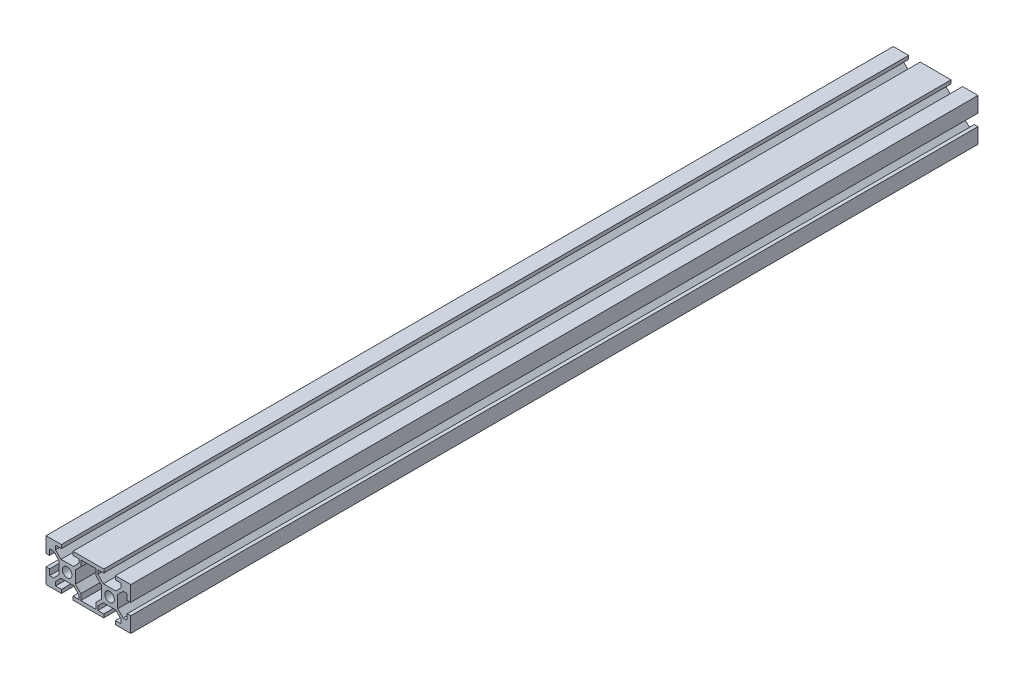
SolidWorks part; units mm, degrees
ref_plane "前视基准面" through (0, 0, 0) normal (0, 0, 1) x (1, 0, 0)
ref_plane "上视基准面" through (0, 0, 0) normal (0, 1, 0) x (1, 0, 0)
ref_plane "右视基准面" through (0, 0, 0) normal (1, 0, 0) x (0, 0, -1)
sketch "草图1" plane through (0, 0, 0) normal (0, 0, 1) x (1, 0, 0)
  line L0 (-4.1, 15) -> (-4.1, 12.5)
  line L1 (-4.3858, -5.8) -> (4.3858, -5.8)
  line L2 (-5.8, -4.3858) -> (-5.8, 4.3858)
  line L3 (-4.3858, 5.8) -> (4.3858, 5.8)
  line L4 (5.8, -4.3858) -> (5.8, 4.3858)
  line L5 (-9.6642, 8.25) -> (-12.5, 8.25)
  line L6 (-8.25, -12.5) -> (-4.1, -12.5)
  line L7 (-15, -15) -> (-4.1, -15)
  line L8 (-15, -15) -> (-15, -4.1)
  line L9 (-8.25, 15) -> (-4.1, 15)
  line L10 (9.6642, -8.25) -> (9.6642, -12.5)
  line L11 (-8.25, 9.6642) -> (-8.25, 12.5)
  line L12 (-8.25, 15) -> (-15, 15)
  line L13 (9.6642, -12.5) -> (20.3358, -12.5)
  line L14 (8.25, 9.6642) -> (8.25, 12.5)
  line L15 (8.25, 15) -> (15, 15)
  line L16 (20.3358, -12.5) -> (20.3358, -8.25)
  line L17 (9.6642, 8.25) -> (9.6642, 12.5)
  line L18 (8.25, -9.6642) -> (8.25, -12.5)
  line L19 (8.25, -15) -> (15, -15)
  line L20 (9.6642, 12.5) -> (20.3358, 12.5)
  line L21 (-15, 8.25) -> (-15, 15)
  line L22 (-9.6642, -8.25) -> (-12.5, -8.25)
  line L23 (-8.25, -9.6642) -> (-8.25, -12.5)
  line L24 (-8.25, -15) -> (-15, -15)
  line L25 (-15, -8.25) -> (-15, -15)
  line L26 (-12.5, -8.25) -> (-12.5, -4.1)
  line L27 (-8.25, 12.5) -> (-4.1, 12.5)
  line L28 (20.3358, 12.5) -> (20.3358, 8.25)
  line L29 (-8.25, 9.6642) -> (-4.3858, 5.8)
  line L30 (-9.6642, 8.25) -> (-5.8, 4.3858)
  line L31 (8.25, 9.6642) -> (4.3858, 5.8)
  line L32 (9.6642, 8.25) -> (5.8, 4.3858)
  line L33 (4.3858, -5.8) -> (8.25, -9.6642)
  line L34 (-5.8, -4.3858) -> (-9.6642, -8.25)
  line L35 (4.1, 15) -> (4.1, 12.5)
  line L36 (5.8, -4.3858) -> (9.6642, -8.25)
  line L37 (-4.3858, -5.8) -> (-8.25, -9.6642)
  line L38 (4.1, 15) -> (15, 15)
  line L39 (4.1, 12.5) -> (8.25, 12.5)
  line L40 (-4.1, -12.5) -> (-4.1, -15)
  line L41 (4.1, -15) -> (15, -15)
  line L42 (4.1, -12.5) -> (8.25, -12.5)
  line L43 (4.1, -12.5) -> (4.1, -15)
  line L44 (-15, 4.1) -> (-12.5, 4.1)
  line L45 (-15, -4.1) -> (-12.5, -4.1)
  line L46 (-15, 4.1) -> (-15, 15)
  line L47 (-12.5, 4.1) -> (-12.5, 8.25)
  line L48 (-15, -15) -> (0, 0) construction
  line L52 (-15, 8.25) -> (-15, 4.1)
  line L54 (8.25, -15) -> (4.1, -15)
  line L55 (8.25, 15) -> (4.1, 15)
  line L56 (38.25, 9.6642) -> (38.25, 12.5)
  line L57 (21.75, 9.6642) -> (25.6142, 5.8)
  line L58 (38.25, -15) -> (34.1, -15)
  line L59 (25.6142, 5.8) -> (34.3858, 5.8)
  line L61 (34.1, 15) -> (34.1, 12.5)
  line L62 (21.75, 15) -> (15, 15)
  line L63 (39.6642, 8.25) -> (35.8, 4.3858)
  line L64 (45, 4.1) -> (45, 15)
  line L65 (38.25, 15) -> (45, 15)
  line L66 (39.6642, -8.25) -> (42.5, -8.25)
  line L68 (45, -15) -> (45, -4.1)
  line L69 (38.25, -9.6642) -> (38.25, -12.5)
  line L70 (35.8, -4.3858) -> (39.6642, -8.25)
  line L71 (42.5, -4.1) -> (45, -4.1)
  line L72 (45, 8.25) -> (45, 15)
  line L73 (42.5, -8.25) -> (42.5, -4.1)
  line L74 (38.25, 15) -> (34.1, 15)
  line L77 (34.1, 12.5) -> (38.25, 12.5)
  line L79 (38.25, 9.6642) -> (34.3858, 5.8)
  line L80 (34.1, -12.5) -> (38.25, -12.5)
  line L82 (35.8, -4.3858) -> (35.8, 4.3858)
  line L83 (21.75, -15) -> (15, -15)
  line L84 (34.1, -15) -> (45, -15)
  line L85 (21.75, -12.5) -> (25.9, -12.5)
  line L86 (39.6642, 8.25) -> (42.5, 8.25)
  line L87 (24.2, -4.3858) -> (20.3358, -8.25)
  line L88 (42.5, 4.1) -> (45, 4.1)
  line L89 (21.75, 12.5) -> (25.9, 12.5)
  line L90 (15, 4.1) -> (17.5, 4.1)
  line L91 (25.9, 15) -> (25.9, 12.5)
  line L92 (21.75, 9.6642) -> (21.75, 12.5)
  line L93 (45, -8.25) -> (45, -15)
  line L94 (34.1, 15) -> (45, 15)
  line L96 (20.3358, 8.25) -> (24.2, 4.3858)
  line L97 (34.1, -12.5) -> (34.1, -15)
  line L98 (45, 8.25) -> (45, 4.1)
  line L99 (24.2, -4.3858) -> (24.2, 4.3858)
  line L100 (21.75, -9.6642) -> (21.75, -12.5)
  line L101 (25.9, -12.5) -> (25.9, -15)
  line L102 (15, -15) -> (25.9, -15)
  line L103 (34.3858, -5.8) -> (38.25, -9.6642)
  line L104 (42.5, 4.1) -> (42.5, 8.25)
  line L105 (25.6142, -5.8) -> (34.3858, -5.8)
  line L108 (21.75, 15) -> (25.9, 15)
  line L109 (38.25, -15) -> (45, -15)
  line L110 (25.6142, -5.8) -> (21.75, -9.6642)
  circle A0 centre (0, 0) radius 3.4
  circle A1 centre (30, 0) radius 3.4
extrude "凸台-拉伸1" add sketch "草图1" along normal blind 600
